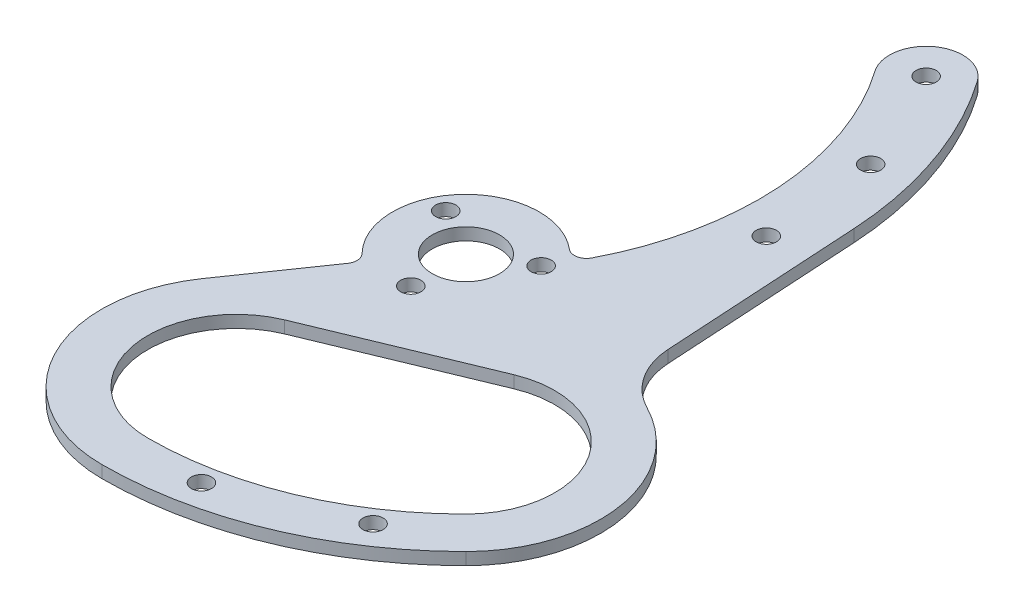
SolidWorks part; units mm, degrees
ref_plane "Спереди" through (0, 0, 0) normal (0, 0, 1) x (1, 0, 0)
ref_plane "Сверху" through (0, 0, 0) normal (0, 1, 0) x (1, 0, 0)
ref_plane "Справа" through (0, 0, 0) normal (1, 0, 0) x (0, 0, -1)
sketch "Эскиз1" plane through (0, 0, 0) normal (0, 1, 0) x (1, 0, 0)
  line L0 (0, -52) -> (0, -59.5) construction
  line L1 (36.7696, -36.7696) -> (42.0729, -42.0729) construction
  line L2 (0, -52) -> (0, 0) construction
  line L3 (0, 0) -> (0, 63.6396) construction
  line L4 (-31.8198, 31.8198) -> (0, 63.6396) construction
  line L5 (-7.3581, -9.4794) -> (-18.0878, -24.9768)
  line L6 (0, 0) -> (36.7696, -36.7696) construction
  line L7 (19.8995, -48.0417) -> (22.7697, -54.9708) construction
  line L8 (0, 0) -> (-7.7942, 4.5) construction
  line L9 (-18.0878, -24.9768) -> (30.4512, -4.8712) construction
  line L10 (0, 0) -> (7.7942, 4.5) construction
  line L11 (-31.8198, 31.8198) -> (0, 0) construction
  line L12 (-5.5489, -24.1037) -> (20.9676, -13.1203)
  line L13 (30.4512, -4.8712) -> (28.0759, 35.3565)
  line L14 (-31.8198, 31.8198) -> (0, 63.6396) construction
  line L15 (28.1802, 31.8198) -> (16.1802, 31.8198) construction
  line L16 (10.73, -53.9432) -> (0, 0) construction
  line L17 (0, 0) -> (30.5564, -45.7308) construction
  line L18 (-31.8198, 31.8198) -> (17.3293, 66.2344) construction
  arc A0 (42.0729, -42.0729) -> (0, -59.5) centre (0, 0) cw
  arc A1 (0, -52) -> (36.7696, -36.7696) centre (0, 0) ccw
  arc A2 (0, -55) -> (21.0476, -50.8134) centre (0, 0) ccw construction
  circle A3 centre (10.73, -53.9432) radius 1.65
  circle A4 centre (30.5564, -45.7308) radius 1.65
  arc A5 (7.4995, 59.3515) -> (9.4794, 7.3581) centre (-31.8198, 31.8198) cw
  circle A6 centre (0, 0) radius 5.5
  arc A7 (17.3293, 66.2344) -> (28.0759, 35.3565) centre (-31.8198, 31.8198) cw
  arc A8 (22.1802, 31.8198) -> (12.4144, 62.7929) centre (-31.8198, 31.8198) ccw construction
  arc A9 (7.4995, 59.3515) -> (17.3293, 66.2344) centre (12.4144, 62.7929) cw
  arc A10 (9.4794, 7.3581) -> (-7.3581, -9.4794) centre (-31.8198, 31.8198) cw construction
  arc A11 (36.7696, -36.7696) -> (20.9676, -13.1203) centre (26.5165, -26.5165) ccw
  circle A13 centre (0, 0) radius 9 construction
  circle A14 centre (0, -9) radius 1.65
  circle A15 centre (-7.7942, 4.5) radius 1.65
  arc A16 (42.0729, -42.0729) -> (30.4512, -4.8712) centre (26.5165, -26.5165) ccw
  arc A18 (0, -52) -> (-5.5489, -24.1037) centre (0, -37.5) cw
  circle A19 centre (7.7942, 4.5) radius 1.65
  arc A20 (0, 0) -> (-4.1195, -3.6442) centre (-31.8198, 31.8198) ccw construction
  arc A22 (9.4794, 7.3581) -> (-7.3581, -9.4794) centre (0, 0) ccw
  arc A23 (0, -59.5) -> (-18.0878, -24.9768) centre (0, -37.5) cw
  point P1 (22.1802, 31.8198)
  dimension "D3" = 52
  dimension "D4" = 3.3
  dimension "D7" = 90
  dimension "D8" = 120
  dimension "D9" = 11
  dimension "D10" = 90
  dimension "D11" = 18
  dimension "D12" = 48
  dimension "D13" = 22.5
  dimension "D14" = 60
  dimension "D20" = 22
  dimension "D16" = 29
  dimension "D17" = 12
  dimension "D18" = 10
  dimension "D5" = 55
  dimension "D6" = 45
  dimension "D15" = 120
extrude "Бобышка-Вытянуть1" add sketch "Эскиз1" along normal blind 2
sketch "Эскиз2" plane through (0, 0, 0) normal (0, -1, 0) x (1, 0, 0)
  line L0 (-31.8198, -31.8198) -> (0, 0) construction
  line L1 (-31.8198, -31.8198) -> (22.9872, -27.0248) construction
  line L2 (-31.8198, -31.8198) -> (13.7419, -63.7224) construction
  line L3 (-31.8198, -31.8198) -> (22.5978, -46.401) construction
  circle A0 centre (21.9747, -27.1134) radius 1.65
  circle A1 centre (12.4144, -62.7929) radius 1.65
  circle A2 centre (20.3402, -45.796) radius 1.65
  circle A3 centre (-31.8198, -31.8198) radius 54 construction
  point P0 (-31.8198, -31.8198)
  dimension "D3" = 3.3
  dimension "D4" = 3.3
  dimension "D5" = 3.3
  dimension "D1" = 40
  dimension "D2" = 60
  dimension "D6" = 80
extrude "Вырез-Вытянуть1" cut sketch "Эскиз2" against normal through all
fillet "Скругление1" radius 2 2 edges at (9.4794, 1, -7.3581) (-7.3581, 1, 9.4794)
fillet "Скругление2" radius 12 1 edges at (30.4512, 1, 4.8712)
